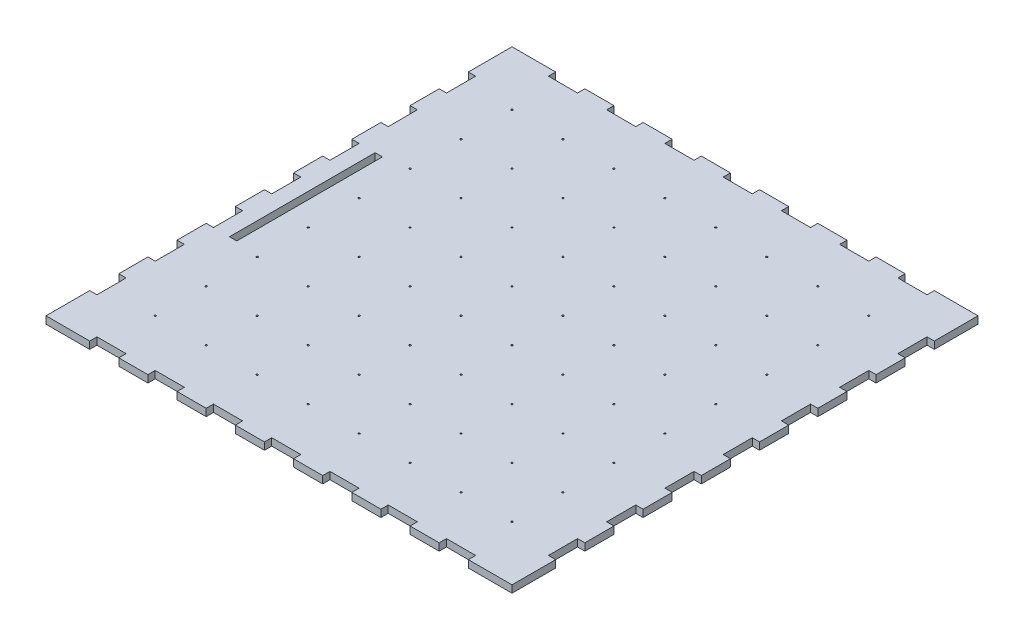
SolidWorks part; units mm, degrees
material "Oak"
ref_plane "Front Plane" through (0, 0, 0) normal (0, 0, 1) x (1, 0, 0)
ref_plane "Top Plane" through (0, 0, 0) normal (0, 1, 0) x (1, 0, 0)
ref_plane "Right Plane" through (0, 0, 0) normal (1, 0, 0) x (0, 0, -1)
sketch "Sketch1" plane through (0, 0, 0) normal (0, 1, 0) x (1, 0, 0)
  line L1 (80, 80) -> (-80, 80)
  line L2 (80, 80) -> (80, -80)
  line L3 (80, -80) -> (-80, -80)
  line L4 (-80, 80) -> (-80, -80)
  line L5 (80, 80) -> (-80, -80) construction
  line L6 (80, -80) -> (-80, 80) construction
  point P0 (0, 0)
  dimension "D1" = 160
extrude "Boss-Extrude1" add sketch "Sketch1" along normal mid plane 2.5
sketch "Sketch3" plane through (0, 1.25, 0) normal (0, 1, 0) x (1, 0, 0)
  line L0 (-61.25, -61.25) -> (-43.75, -61.25) construction
  line L1 (-61.25, -61.25) -> (-61.25, -43.75) construction
  circle A0 centre (-61.25, -61.25) radius 0.3
  circle A1 centre (-43.75, -61.25) radius 0.3
  circle A2 centre (-26.25, -61.25) radius 0.3
  circle A3 centre (-8.75, -61.25) radius 0.3
  circle A4 centre (8.75, -61.25) radius 0.3
  circle A5 centre (26.25, -61.25) radius 0.3
  circle A6 centre (43.75, -61.25) radius 0.3
  circle A7 centre (61.25, -61.25) radius 0.3
  circle A8 centre (-43.75, -43.75) radius 0.3
  circle A9 centre (-26.25, -43.75) radius 0.3
  circle A10 centre (-8.75, -43.75) radius 0.3
  circle A11 centre (8.75, -43.75) radius 0.3
  circle A12 centre (26.25, -43.75) radius 0.3
  circle A13 centre (43.75, -43.75) radius 0.3
  circle A14 centre (61.25, -43.75) radius 0.3
  circle A15 centre (-43.75, -26.25) radius 0.3
  circle A16 centre (-26.25, -26.25) radius 0.3
  circle A17 centre (-8.75, -26.25) radius 0.3
  circle A18 centre (8.75, -26.25) radius 0.3
  circle A19 centre (26.25, -26.25) radius 0.3
  circle A20 centre (43.75, -26.25) radius 0.3
  circle A21 centre (61.25, -26.25) radius 0.3
  circle A22 centre (-43.75, -8.75) radius 0.3
  circle A23 centre (-26.25, -8.75) radius 0.3
  circle A24 centre (-8.75, -8.75) radius 0.3
  circle A25 centre (8.75, -8.75) radius 0.3
  circle A26 centre (26.25, -8.75) radius 0.3
  circle A27 centre (43.75, -8.75) radius 0.3
  circle A28 centre (61.25, -8.75) radius 0.3
  circle A29 centre (-43.75, 8.75) radius 0.3
  circle A30 centre (-26.25, 8.75) radius 0.3
  circle A31 centre (-8.75, 8.75) radius 0.3
  circle A32 centre (8.75, 8.75) radius 0.3
  circle A33 centre (26.25, 8.75) radius 0.3
  circle A34 centre (43.75, 8.75) radius 0.3
  circle A35 centre (61.25, 8.75) radius 0.3
  circle A36 centre (-43.75, 26.25) radius 0.3
  circle A37 centre (-26.25, 26.25) radius 0.3
  circle A38 centre (-8.75, 26.25) radius 0.3
  circle A39 centre (8.75, 26.25) radius 0.3
  circle A40 centre (26.25, 26.25) radius 0.3
  circle A41 centre (43.75, 26.25) radius 0.3
  circle A42 centre (61.25, 26.25) radius 0.3
  circle A43 centre (-43.75, 43.75) radius 0.3
  circle A44 centre (-26.25, 43.75) radius 0.3
  circle A45 centre (-8.75, 43.75) radius 0.3
  circle A46 centre (8.75, 43.75) radius 0.3
  circle A47 centre (26.25, 43.75) radius 0.3
  circle A48 centre (43.75, 43.75) radius 0.3
  circle A49 centre (61.25, 43.75) radius 0.3
  circle A50 centre (-43.75, 61.25) radius 0.3
  circle A51 centre (-26.25, 61.25) radius 0.3
  circle A52 centre (-8.75, 61.25) radius 0.3
  circle A53 centre (8.75, 61.25) radius 0.3
  circle A54 centre (26.25, 61.25) radius 0.3
  circle A55 centre (43.75, 61.25) radius 0.3
  circle A56 centre (61.25, 61.25) radius 0.3
  circle A57 centre (-61.25, -43.75) radius 0.3
  circle A58 centre (-61.25, -26.25) radius 0.3
  circle A59 centre (-61.25, -8.75) radius 0.3
  circle A60 centre (-61.25, 8.75) radius 0.3
  circle A61 centre (-61.25, 26.25) radius 0.3
  circle A62 centre (-61.25, 43.75) radius 0.3
  circle A63 centre (-61.25, 61.25) radius 0.3
  dimension "D7" = 0.6
  dimension "D3" = 17.5
  dimension "D4" = 17.5
  dimension "D5" = 8.75
  dimension "D6" = 8.75
  dimension "D1" = 8
  dimension "D2" = 8
extrude "Cut-Extrude2" cut sketch "Sketch3" against normal through all
sketch "Sketch4" plane through (0, 1.25, 0) normal (0, 1, 0) x (1, 0, 0)
  line L5 (80, -80) -> (80, 80) construction
  line L6 (77.5, 77.5) -> (-77.5, 77.5)
  line L11 (65, 77.5) -> (65, 80)
  line L39 (77.5, 77.5) -> (77.5, -77.5)
  line L125 (77.5, -77.5) -> (-77.5, -77.5)
  line L126 (-77.5, 77.5) -> (-77.5, -77.5)
  line L127 (77.5, 77.5) -> (-77.5, -77.5) construction
  line L128 (77.5, -77.5) -> (-77.5, 77.5) construction
  line L129 (77.5, -65) -> (80, -65)
  line L130 (77.5, -65) -> (77.5, -55)
  line L131 (77.5, -55) -> (80, -55)
  line L132 (80, -65) -> (80, -55)
  line L133 (77.5, -45) -> (77.5, -35)
  line L134 (77.5, -45) -> (80, -45)
  line L135 (80, -45) -> (80, -35)
  line L136 (77.5, -35) -> (80, -35)
  line L137 (77.5, -25) -> (77.5, -15)
  line L138 (77.5, -25) -> (80, -25)
  line L139 (80, -25) -> (80, -15)
  line L140 (77.5, -15) -> (80, -15)
  line L141 (77.5, -5) -> (77.5, 5)
  line L142 (77.5, -5) -> (80, -5)
  line L143 (80, -5) -> (80, 5)
  line L144 (77.5, 5) -> (80, 5)
  line L145 (77.5, 15) -> (77.5, 25)
  line L146 (77.5, 15) -> (80, 15)
  line L147 (80, 15) -> (80, 25)
  line L148 (77.5, 25) -> (80, 25)
  line L149 (77.5, 35) -> (77.5, 45)
  line L150 (77.5, 35) -> (80, 35)
  line L151 (80, 35) -> (80, 45)
  line L152 (77.5, 45) -> (80, 45)
  line L153 (77.5, 55) -> (77.5, 65)
  line L154 (77.5, 55) -> (80, 55)
  line L155 (80, 55) -> (80, 65)
  line L156 (77.5, 65) -> (80, 65)
  line L157 (77.5, -65) -> (77.5, -45) construction
  line L158 (55, 80) -> (65, 80)
  line L159 (55, 77.5) -> (55, 80)
  line L160 (55, 77.5) -> (65, 77.5)
  line L161 (45, 77.5) -> (45, 80)
  line L162 (35, 80) -> (45, 80)
  line L163 (35, 77.5) -> (35, 80)
  line L164 (35, 77.5) -> (45, 77.5)
  line L165 (25, 77.5) -> (25, 80)
  line L166 (15, 80) -> (25, 80)
  line L167 (15, 77.5) -> (15, 80)
  line L168 (15, 77.5) -> (25, 77.5)
  line L169 (5, 77.5) -> (5, 80)
  line L170 (-5, 80) -> (5, 80)
  line L171 (-5, 77.5) -> (-5, 80)
  line L172 (-5, 77.5) -> (5, 77.5)
  line L173 (-15, 77.5) -> (-15, 80)
  line L174 (-25, 80) -> (-15, 80)
  line L175 (-25, 77.5) -> (-25, 80)
  line L176 (-25, 77.5) -> (-15, 77.5)
  line L177 (-35, 77.5) -> (-35, 80)
  line L178 (-45, 80) -> (-35, 80)
  line L179 (-45, 77.5) -> (-45, 80)
  line L180 (-45, 77.5) -> (-35, 77.5)
  line L181 (-65, 80) -> (-55, 80)
  line L182 (-55, 77.5) -> (-55, 80)
  line L183 (-65, 77.5) -> (-55, 77.5)
  line L184 (-65, 77.5) -> (-65, 80)
  line L185 (-65, -77.5) -> (-65, -80)
  line L186 (-55, -80) -> (-65, -80)
  line L187 (-55, -77.5) -> (-55, -80)
  line L188 (-55, -77.5) -> (-65, -77.5)
  line L189 (-45, -77.5) -> (-45, -80)
  line L190 (-35, -80) -> (-45, -80)
  line L191 (-35, -77.5) -> (-35, -80)
  line L192 (-35, -77.5) -> (-45, -77.5)
  line L193 (-25, -77.5) -> (-25, -80)
  line L194 (-15, -80) -> (-25, -80)
  line L195 (-15, -77.5) -> (-15, -80)
  line L196 (-15, -77.5) -> (-25, -77.5)
  line L197 (-5, -77.5) -> (-5, -80)
  line L198 (5, -80) -> (-5, -80)
  line L199 (5, -77.5) -> (5, -80)
  line L200 (5, -77.5) -> (-5, -77.5)
  line L201 (15, -77.5) -> (15, -80)
  line L202 (25, -80) -> (15, -80)
  line L203 (25, -77.5) -> (25, -80)
  line L204 (25, -77.5) -> (15, -77.5)
  line L205 (35, -77.5) -> (35, -80)
  line L206 (45, -80) -> (35, -80)
  line L207 (45, -77.5) -> (45, -80)
  line L208 (45, -77.5) -> (35, -77.5)
  line L209 (65, -80) -> (55, -80)
  line L210 (55, -77.5) -> (55, -80)
  line L211 (65, -77.5) -> (55, -77.5)
  line L212 (65, -77.5) -> (65, -80)
  line L213 (-77.5, 65) -> (-80, 65)
  line L214 (-77.5, 65) -> (-77.5, 55)
  line L215 (-77.5, 55) -> (-80, 55)
  line L216 (-80, 65) -> (-80, 55)
  line L217 (-77.5, 45) -> (-77.5, 35)
  line L218 (-77.5, 45) -> (-80, 45)
  line L219 (-80, 45) -> (-80, 35)
  line L220 (-77.5, 35) -> (-80, 35)
  line L221 (-77.5, 25) -> (-77.5, 15)
  line L222 (-77.5, 25) -> (-80, 25)
  line L223 (-80, 25) -> (-80, 15)
  line L224 (-77.5, 15) -> (-80, 15)
  line L225 (-77.5, 5) -> (-77.5, -5)
  line L226 (-77.5, 5) -> (-80, 5)
  line L227 (-80, 5) -> (-80, -5)
  line L228 (-77.5, -5) -> (-80, -5)
  line L229 (-77.5, -15) -> (-77.5, -25)
  line L230 (-77.5, -15) -> (-80, -15)
  line L231 (-80, -15) -> (-80, -25)
  line L232 (-77.5, -25) -> (-80, -25)
  line L233 (-77.5, -35) -> (-77.5, -45)
  line L234 (-77.5, -35) -> (-80, -35)
  line L235 (-80, -35) -> (-80, -45)
  line L236 (-77.5, -45) -> (-80, -45)
  line L237 (-77.5, -55) -> (-77.5, -65)
  line L238 (-77.5, -55) -> (-80, -55)
  line L239 (-80, -55) -> (-80, -65)
  line L240 (-77.5, -65) -> (-80, -65)
  point P0 (0, 0)
  point P12 (80, 0)
  dimension "D1" = 155
  dimension "D2" = 10
  dimension "D4" = 20
  dimension "D3" = 7
extrude "Cut-Extrude3" cut sketch "Sketch4" against normal through all
sketch "Sketch5" plane through (0, 1.25, 0) normal (0, 1, 0) x (1, 0, 0)
  line L0 (-80, 15) -> (-80, 5) construction
  line L1 (-69.5, 25) -> (-72, 25)
  line L2 (-69.5, 25) -> (-69.5, -25)
  line L3 (-69.5, -25) -> (-72, -25)
  line L4 (-72, 25) -> (-72, -25)
  point P4 (-69.5, 0)
  dimension "D1" = 2.5
  dimension "D2" = 50
  dimension "D3" = 8
extrude "Cut-Extrude4" cut sketch "Sketch5" against normal up to next
equation "\"thick\"=0.25"
equation "\"D1@Boss-Extrude1\"=\"thick\""
equation "\"hole_length\"= 1"
equation "\"length\"=16"
equation "\"D1@Sketch1\"=\"length\""
equation "\"dist\"=1.75"
equation "\"D3@Sketch3\"=\"dist\""
equation "\"D4@Sketch3\"=\"dist\""
equation "\"D6@Sketch3\"=\"dist\"/2"
equation "\"D5@Sketch3\"=\"D6@Sketch3\""
equation "\"D2@Sketch4\"=\"hole_length\""
equation "\"D1@Sketch5\"=\"thick\""
